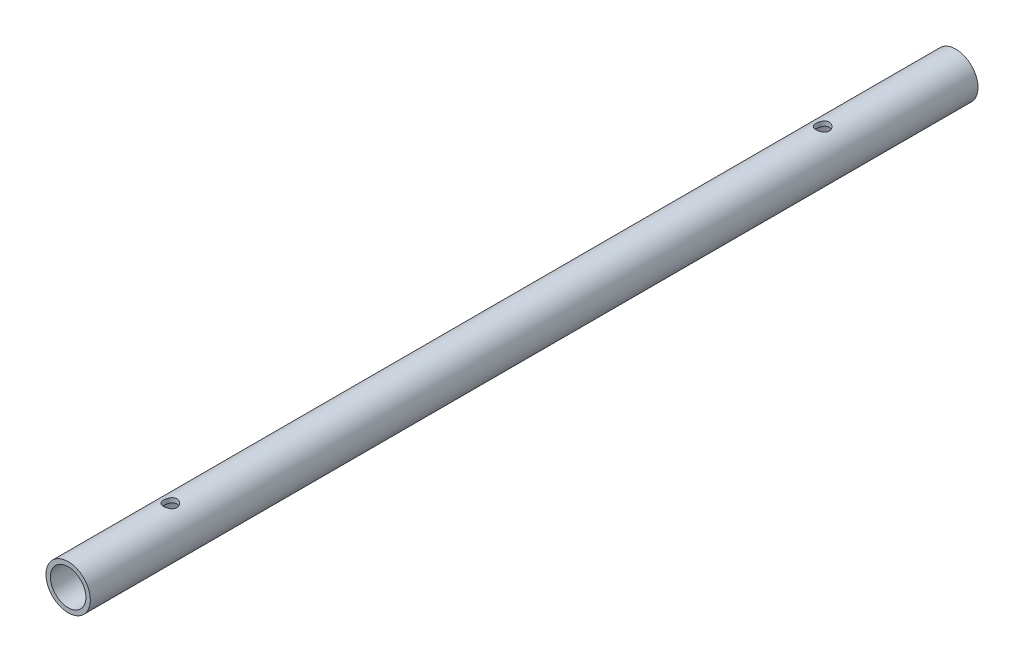
SolidWorks part; units mm, degrees
material "Thornel Mat VMA"
ref_plane "前视基准面" through (0, 0, 0) normal (0, 0, 1) x (1, 0, 0)
ref_plane "上视基准面" through (0, 0, 0) normal (0, 1, 0) x (1, 0, 0)
ref_plane "右视基准面" through (0, 0, 0) normal (1, 0, 0) x (0, 0, -1)
other "Configuration Table"
sketch "草图1" plane through (0, 0, 0) normal (0, 0, 1) x (1, 0, 0)
  circle A0 centre (0, 0) radius 5
  circle A1 centre (0, 0) radius 4
  dimension "D1" = 10
  dimension "D2" = 1
extrude "凸台-拉伸1" add sketch "草图1" along normal blind 200
sketch "草图2" plane through (0, 0, 0) normal (0, 1, 0) x (1, 0, 0)
  line L0 (5, -200) -> (5, 0) construction
  line L1 (-5, -200) -> (5, -200) construction
  circle A0 centre (0, -177) radius 1.5
  circle A1 centre (0, -30) radius 1.5
  dimension "D1" = 3
  dimension "D5" = 3
  dimension "D2" = 5
  dimension "D3" = 23
  dimension "D4" = 30
extrude "切除-拉伸1" cut sketch "草图2" along normal through all
